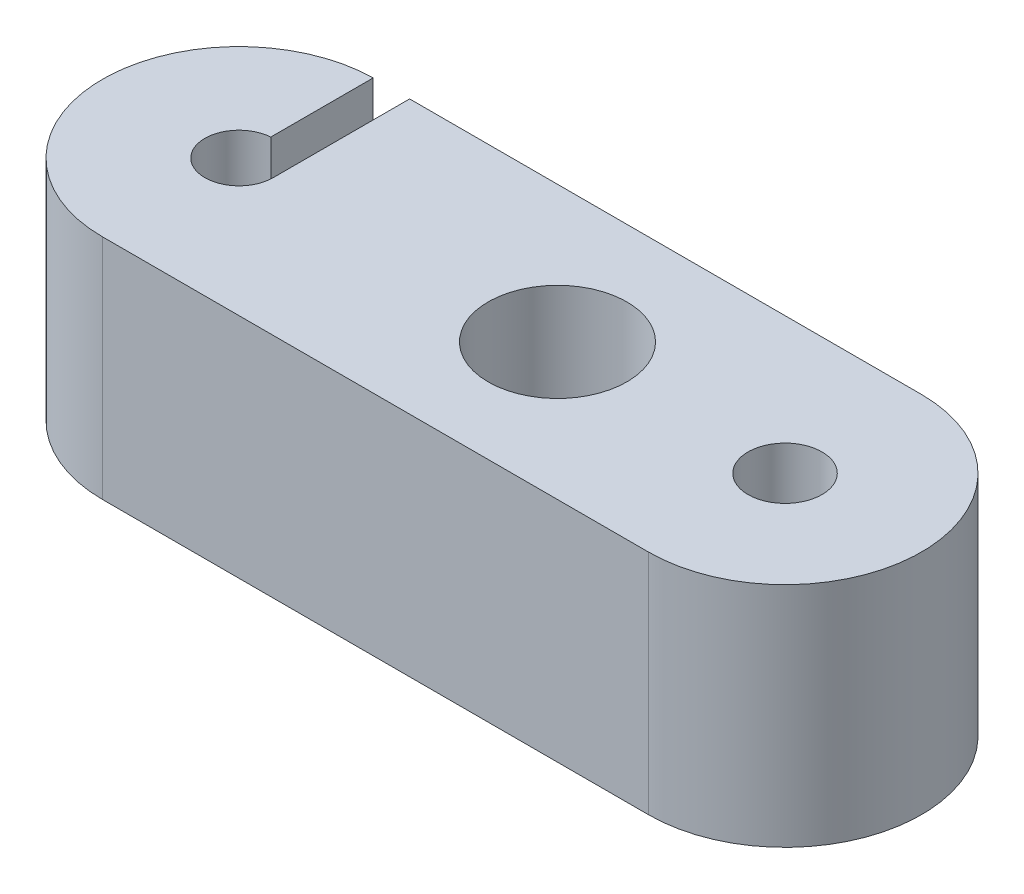
SolidWorks part; units mm, degrees
ref_plane "Front Plane" through (0, 0, 0) normal (0, 0, 1) x (1, 0, 0)
ref_plane "Top Plane" through (0, 0, 0) normal (0, 1, 0) x (1, 0, 0)
ref_plane "Right Plane" through (0, 0, 0) normal (1, 0, 0) x (0, 0, -1)
sketch "Sketch1" plane through (0, 0, 0) normal (0, 1, 0) x (1, 0, 0)
  line L0 (-3, 0) -> (3, 0) construction
  line L1 (-3, 1.5) -> (3, 1.5)
  line L2 (-3, -1.5) -> (3, -1.5)
  arc A0 (-3, 1.5) -> (-3, -1.5) centre (-3, 0) ccw
  arc A1 (3, -1.5) -> (3, 1.5) centre (3, 0) ccw
  circle A2 centre (0.5, 0) radius 0.762
  circle A3 centre (3, 0) radius 0.4064
  circle A4 centre (-3, 0) radius 0.375
  point P2 (0, 0)
  dimension "D3" = 0.8128
  dimension "D5" = 1.524
  dimension "D6" = 0.75
  dimension "D2" = 3
  dimension "D4" = 2.5
  dimension "D1" = 3.5
extrude "Boss-Extrude1" add sketch "Sketch1" along normal blind 2.5
sketch "Sketch2" plane through (0, 0, 0) normal (0, -1, 0) x (1, 0, 0)
  line L0 (-3.375, 0) -> (-2.625, 0) construction
  line L1 (-3, 0) -> (-3, -1.5) construction
  line L2 (-2.625, 0) -> (-3.025, 0)
  line L3 (-2.625, 0) -> (-2.625, -2.5)
  line L4 (-3.025, 0) -> (-3.025, -2.5)
  line L5 (-2.625, -2.5) -> (-3.025, -2.5)
  line L6 (3, -1.5) -> (-3, -1.5) construction
  circle A0 centre (-3, 0) radius 0.375 construction
  dimension "D1" = 0.4
  dimension "D2" = 1
extrude "Cut-Extrude1" cut sketch "Sketch2" against normal through all contours L3 L5 L4 L2
equation "\"StabilizerRodeHole\"=0.8128"
equation "\"D3@Sketch1\"=\"StabilizerRodeHole\""
